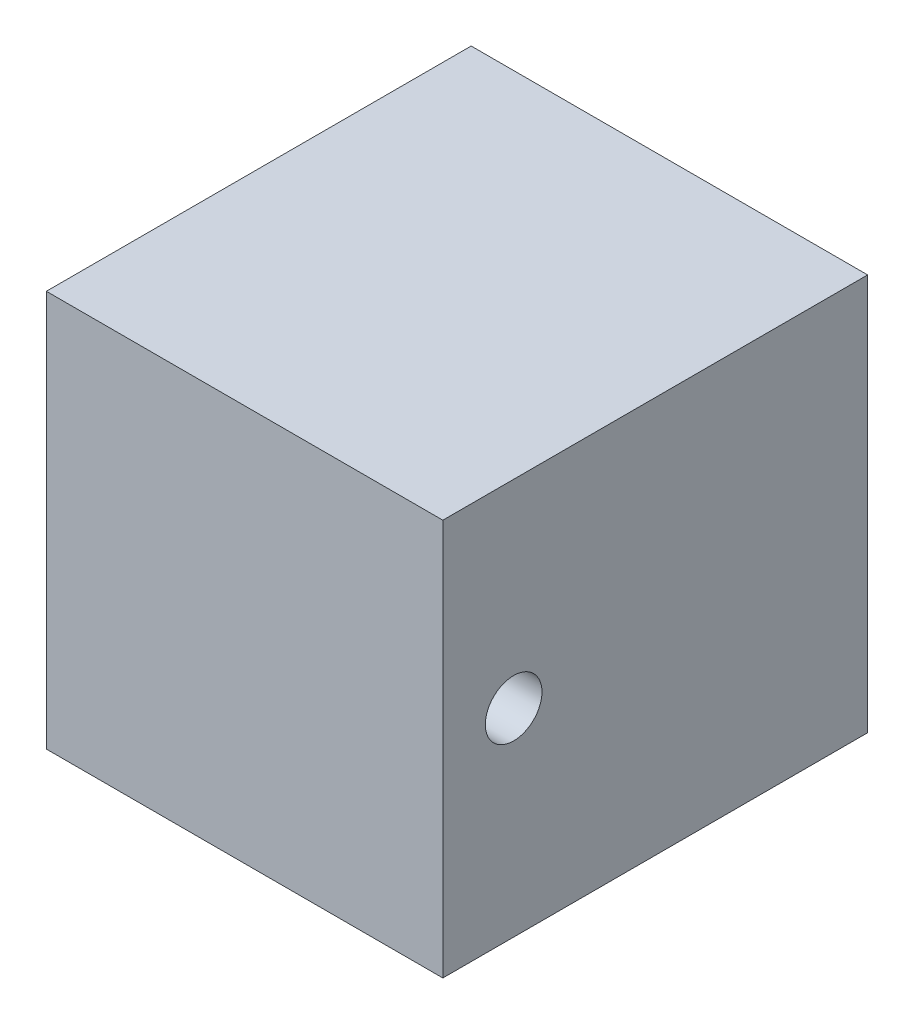
SolidWorks part; units mm, degrees
ref_plane "前视基准面" through (0, 0, 0) normal (0, 0, 1) x (1, 0, 0)
ref_plane "上视基准面" through (0, 0, 0) normal (0, 1, 0) x (1, 0, 0)
ref_plane "右视基准面" through (0, 0, 0) normal (1, 0, 0) x (0, 0, -1)
sketch "草图1" plane through (0, 0, 0) normal (0, 0, 1) x (1, 0, 0)
  line L1 (0, 0) -> (14, 0)
  line L2 (0, 0) -> (0, 14)
  line L3 (0, 14) -> (14, 14)
  line L4 (14, 0) -> (14, 14)
  line L5 (1, 1) -> (13, 1)
  line L6 (1, 1) -> (1, 13)
  line L7 (1, 13) -> (13, 13)
  line L8 (13, 1) -> (13, 13)
  point P5 (1, 1)
extrude "凸台-拉伸1" add sketch "草图1" along normal blind 10
sketch "草图2" plane through (0, 0, 10) normal (0, 0, 1) x (1, 0, 0)
  line L1 (0, 14) -> (14, 14)
  line L2 (0, 14) -> (0, 0)
  line L3 (0, 0) -> (14, 0)
  line L4 (14, 14) -> (14, 0)
extrude "凸台-拉伸2" add sketch "草图2" along normal blind 5
sketch "草图3" plane through (14, 0, 0) normal (1, 0, 0) x (0, 0, -1)
  circle A0 centre (-12.5, 7) radius 1
  point P0 (-12.5, 7)
extrude "切除-拉伸1" cut sketch "草图3" against normal blind 14
